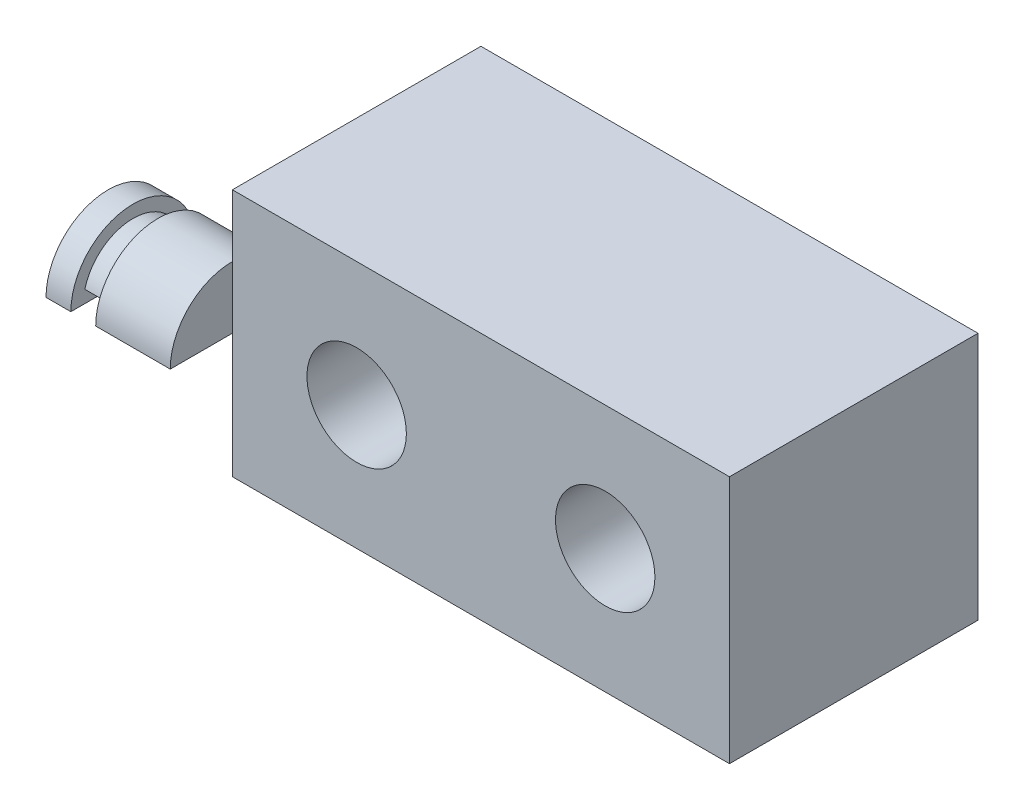
SolidWorks part; units mm, degrees
ref_plane "Front Plane" through (0, 0, 0) normal (0, 0, 1) x (1, 0, 0)
ref_plane "Top Plane" through (0, 0, 0) normal (0, 1, 0) x (1, 0, 0)
ref_plane "Right Plane" through (0, 0, 0) normal (1, 0, 0) x (0, 0, -1)
sketch "Sketch1" plane through (0, 0, 0) normal (0, 1, 0) x (1, 0, 0)
  line L1 (0, 0) -> (50.8, 0)
  line L2 (0, 0) -> (0, 25.4)
  line L3 (0, 25.4) -> (50.8, 25.4)
  line L4 (50.8, 0) -> (50.8, 25.4)
extrude "Boss-Extrude1" add sketch "Sketch1" against normal blind 25.4
sketch "Sketch2" plane through (0, 0, 0) normal (0, 0, 1) x (1, 0, 0)
  circle A0 centre (12.7, -12.7) radius 5.08
  circle A1 centre (38.1, -12.7) radius 5.08
extrude "Cut-Extrude1" cut sketch "Sketch2" against normal blind 13.97
sketch "Sketch3" plane through (0, 0, 0) normal (1, 0, 0) x (0, 0, -1)
  line L0 (-6.35, -12.7) -> (6.35, -12.7)
  arc A0 (-6.35, -12.7) -> (6.35, -12.7) centre (0, -12.7) cw
  point P3 (0, -12.7)
extrude "Boss-Extrude2" add sketch "Sketch3" against normal blind 12.7 from surface at 0 starting at face at (0, -12.7, -12.7)
sketch "Sketch4" plane through (0, 0, 0) normal (1, 0, 0) x (0, 0, -1)
  line L0 (-6.35, -12.7) -> (6.35, -12.7)
  line L2 (-4.9187, -11.43) -> (4.9187, -11.43)
  arc A1 (-4.9187, -11.43) -> (4.9187, -11.43) centre (0, -12.7) cw
  arc A2 (-6.35, -12.7) -> (6.35, -12.7) centre (0, -12.7) cw
  point P3 (0, -12.7)
extrude "Cut-Extrude3" cut sketch "Sketch4" against normal blind 2.54 from offset 7.62
